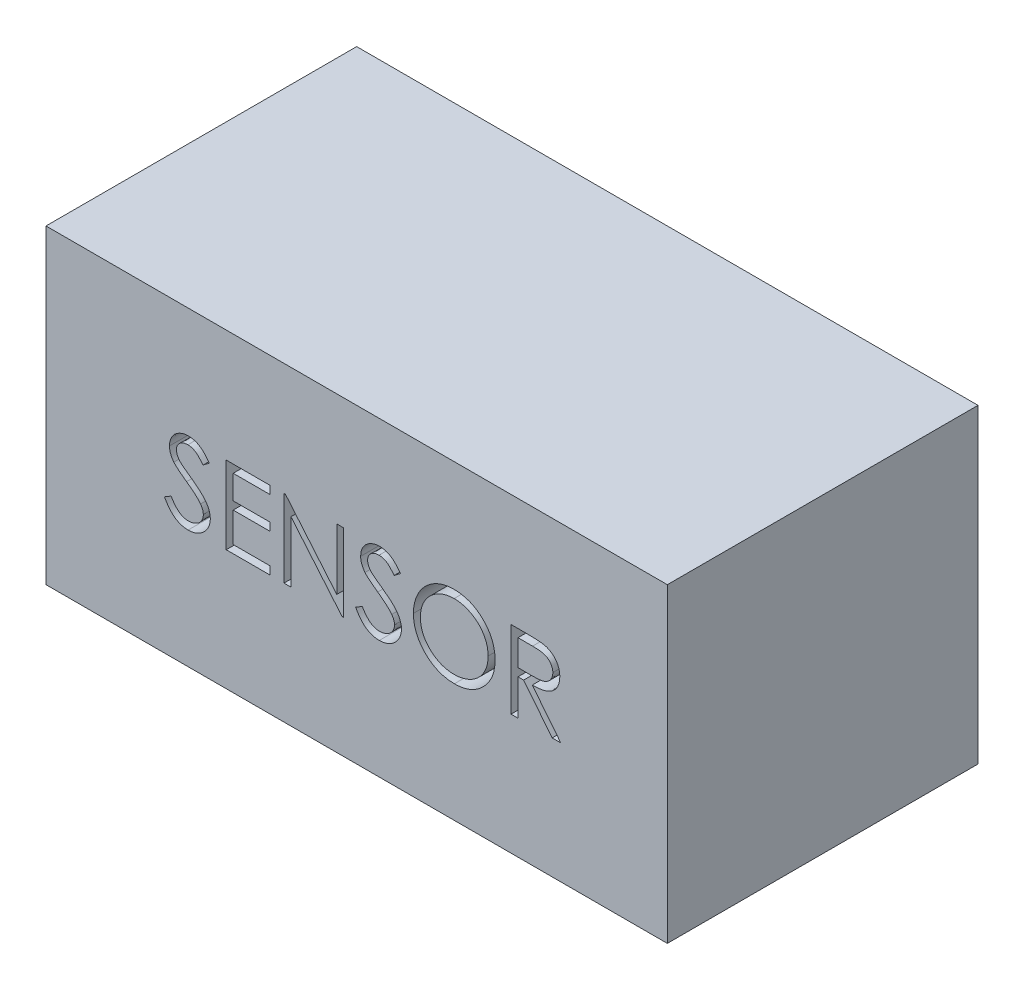
SolidWorks part; units mm, degrees
ref_plane "Front Plane" through (0, 0, 0) normal (0, 0, 1) x (1, 0, 0)
ref_plane "Top Plane" through (0, 0, 0) normal (0, 1, 0) x (1, 0, 0)
ref_plane "Right Plane" through (0, 0, 0) normal (1, 0, 0) x (0, 0, -1)
sketch "Sketch1" plane through (0, 0, 0) normal (1, 0, 0) x (0, 0, -1)
  line L1 (-42.1371, 20.5639) -> (34.0629, 20.5639)
  line L2 (-42.1371, 20.5639) -> (-42.1371, -55.6361)
  line L3 (-42.1371, -55.6361) -> (34.0629, -55.6361)
  line L4 (34.0629, 20.5639) -> (34.0629, -55.6361)
  dimension "D1" = 76.2
  dimension "D2" = 76.2
extrude "Boss-Extrude1" add sketch "Sketch1" along normal blind 152.4
sketch "Sketch2" plane through (0, 0, 42.1371) normal (0, 0, 1) x (1, 0, 0)
  text T0 "SENSOR" font "Century Gothic" height in points 72
extrude "Cut-Extrude1" cut sketch "Sketch2" against normal blind 10
